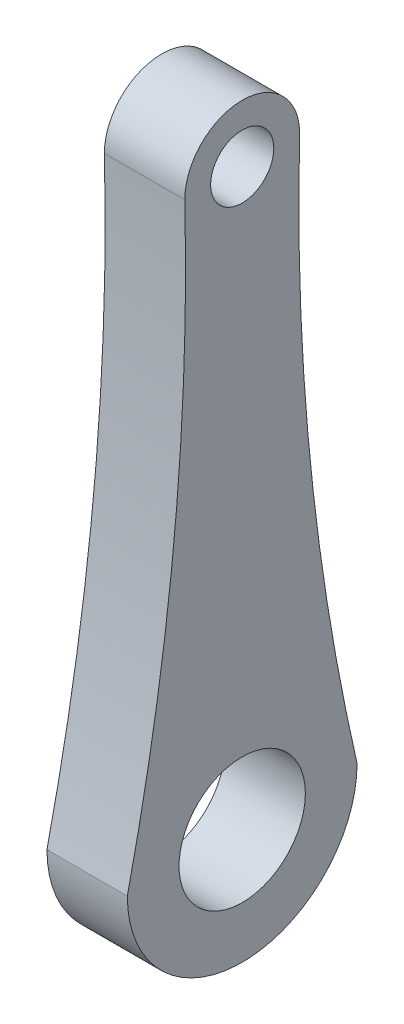
SolidWorks part; units mm, degrees
ref_plane "정면" through (0, 0, 0) normal (0, 0, 1) x (1, 0, 0)
ref_plane "윗면" through (0, 0, 0) normal (0, 1, 0) x (1, 0, 0)
ref_plane "우측면" through (0, 0, 0) normal (1, 0, 0) x (0, 0, -1)
sketch "Sketch1" plane through (0, 0, 0) normal (1, 0, 0) x (0, 0, -1)
  circle A0 centre (0, 0) radius 10
  circle A1 centre (0, 50) radius 5
  arc A2 (-5, 50) -> (-10, 0) centre (-204.9309, 44.7431) cw
  arc A3 (5, 50) -> (10, 0) centre (204.9309, 44.7431) ccw
  dimension "D1" = 20
  dimension "D3" = 10
  dimension "D4" = 200
  dimension "D5" = 200
  dimension "D2" = 50
extrude "Boss-Extrude1" add sketch "Sketch1" along normal blind 7 contours A1 | A3 A1 A2 A0 | A3 A0 A2
hole_wizard "M10 Clearance Hole1" positions "3DSketch2" profile "Sketch2" hole size "M10" standard "Ansi Metric" end condition through all
sketch3d "3DSketch2"
  point P0 (7, 0, 0)
sketch "Sketch2" plane through (7, 0, 0) normal (0, 1, 0) x (0, 0, -1)
  line L0 (0, 0) -> (0, 7)
  line L1 (0, 7) -> (5.5, 7)
  line L2 (5.5, 7) -> (5.5, 0)
  line L5 (5.5, 0) -> (0, 0)
  line L11 (0, -6.35) -> (0, 107.95) construction
  dimension "관통 구멍 지름" = 11
  dimension "관통 구멍 깊이" = 7
hole_wizard "M5 Clearance Hole1" positions "3DSketch4" profile "Sketch3" hole size "M5" standard "Ansi Metric" end condition through all
sketch3d "3DSketch4"
  line L0 (7, 50, 0) -> (0, 50, 0) construction
  point P0 (7, 50, 0)
sketch "Sketch3" plane through (7, 50, 0) normal (0, 1, 0) x (0, 0, -1)
  line L0 (0, 0) -> (0, 7)
  line L1 (0, 7) -> (2.75, 7)
  line L2 (2.75, 7) -> (2.75, 0)
  line L5 (2.75, 0) -> (0, 0)
  line L11 (0, -6.35) -> (0, 107.95) construction
  dimension "관통 구멍 지름" = 5.5
  dimension "관통 구멍 깊이" = 7
